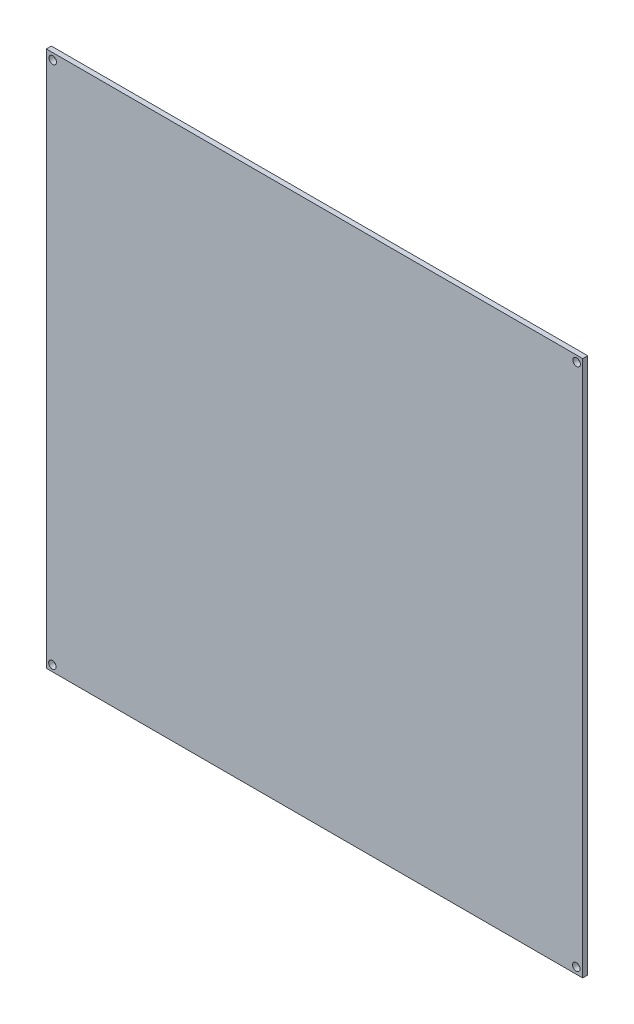
SolidWorks part; units mm, degrees
ref_plane "Front Plane" through (0, 0, 0) normal (0, 0, 1) x (1, 0, 0)
ref_plane "Top Plane" through (0, 0, 0) normal (0, 1, 0) x (1, 0, 0)
ref_plane "Right Plane" through (0, 0, 0) normal (1, 0, 0) x (0, 0, -1)
sketch "Sketch1" plane through (0, 0, 0) normal (0, 0, 1) x (1, 0, 0)
  line L1 (-107, -107) -> (107, -107)
  line L2 (-107, -107) -> (-107, 107)
  line L3 (-107, 107) -> (107, 107)
  line L4 (107, -107) -> (107, 107)
  line L5 (-107, -107) -> (107, 107) construction
  line L6 (-107, 107) -> (107, -107) construction
  circle A0 centre (-104.4348, 104.4348) radius 1.5
  circle A1 centre (104.5652, 104.5652) radius 1.5
  circle A2 centre (104.4348, -104.4348) radius 1.5
  circle A3 centre (-104.5652, -104.5652) radius 1.5
  point P0 (0, 0)
  dimension "D6" = 3
  dimension "D1" = 214
  dimension "D2" = 214
  dimension "D3" = 209
  dimension "D4" = 209
  dimension "D5" = 209
extrude "Boss-Extrude1" add sketch "Sketch1" along normal blind 2
